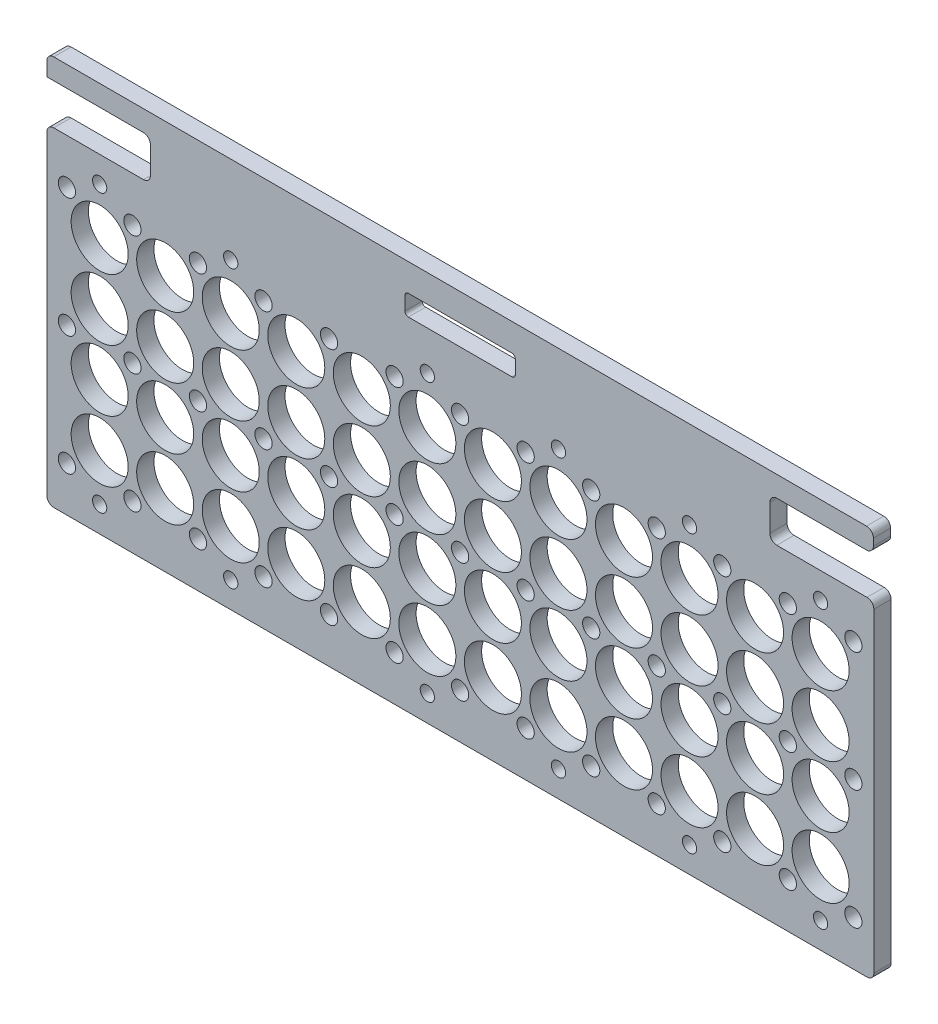
SolidWorks part; units mm, degrees
material "ABS"
ref_plane "X-Y Datum" through (0, 0, 0) normal (0, 0, 1) x (1, 0, 0)
ref_plane "X-Z Datum" through (0, 0, 0) normal (0, 1, 0) x (1, 0, 0)
ref_plane "Y-Z Datum" through (0, 0, 0) normal (1, 0, 0) x (0, 0, -1)
sketch "Sketch1" plane through (0, 0, 0) normal (0, 0, 1) x (1, 0, 0)
  line L1 (-10.2406, 8) -> (78.318, 8)
  line L2 (-10.2406, 8) -> (-10.2406, 16.1972)
  line L7 (-10.2406, 16.1972) -> (78.318, 16.1972)
  line L8 (78.318, 8) -> (78.318, 16.1972)
  line L12 (84.583, 16.1972) -> (87.883, 16.1972) construction
  line L17 (84.583, 4.7) -> (87.883, 4.7) construction
  line L20 (78.318, 0) -> (82.128, 0) construction
  circle A0 centre (0, 0) radius 10.5
  circle A24 centre (0, 0) radius 8 construction
  circle A25 centre (0, 0) radius 4.7 construction
  circle A46 centre (-3.5188, 13.3573) radius 2.5146 construction
  circle A47 centre (-3.5188, 13.3573) radius 1.1913 construction
  circle A78 centre (22.606, 0) radius 10.5
  circle A79 centre (22.606, 0) radius 8 construction
  circle A80 centre (22.606, 0) radius 4.7 construction
  circle A81 centre (45.212, 0) radius 10.5
  circle A82 centre (45.212, 0) radius 8 construction
  circle A83 centre (45.212, 0) radius 4.7 construction
  circle A84 centre (67.818, 0) radius 10.5
  circle A85 centre (67.818, 0) radius 8 construction
  circle A86 centre (67.818, 0) radius 4.7 construction
  circle A87 centre (0, 24.13) radius 10.5
  circle A88 centre (0, 24.13) radius 8 construction
  circle A89 centre (0, 24.13) radius 4.7 construction
  circle A90 centre (22.606, 24.13) radius 10.5
  circle A91 centre (22.606, 24.13) radius 8 construction
  circle A92 centre (22.606, 24.13) radius 4.7 construction
  circle A93 centre (45.212, 24.13) radius 10.5
  circle A94 centre (45.212, 24.13) radius 8 construction
  circle A95 centre (45.212, 24.13) radius 4.7 construction
  circle A96 centre (67.818, 24.13) radius 10.5
  circle A97 centre (67.818, 24.13) radius 8 construction
  circle A98 centre (67.818, 24.13) radius 4.7 construction
  circle A99 centre (0, 48.26) radius 10.5
  circle A100 centre (0, 48.26) radius 8 construction
  circle A101 centre (0, 48.26) radius 4.7 construction
  circle A102 centre (22.606, 48.26) radius 10.5
  circle A103 centre (22.606, 48.26) radius 8 construction
  circle A104 centre (22.606, 48.26) radius 4.7 construction
  circle A105 centre (45.212, 48.26) radius 10.5
  circle A106 centre (45.212, 48.26) radius 8 construction
  circle A107 centre (45.212, 48.26) radius 4.7 construction
  circle A108 centre (67.818, 48.26) radius 10.5
  circle A109 centre (67.818, 48.26) radius 8 construction
  circle A110 centre (67.818, 48.26) radius 4.7 construction
  circle A111 centre (0, 72.39) radius 10.5
  circle A112 centre (0, 72.39) radius 8 construction
  circle A113 centre (0, 72.39) radius 4.7 construction
  circle A114 centre (22.606, 72.39) radius 10.5
  circle A115 centre (22.606, 72.39) radius 8 construction
  circle A116 centre (22.606, 72.39) radius 4.7 construction
  circle A117 centre (45.212, 72.39) radius 10.5
  circle A118 centre (45.212, 72.39) radius 8 construction
  circle A119 centre (45.212, 72.39) radius 4.7 construction
  circle A120 centre (67.818, 72.39) radius 10.5
  circle A121 centre (67.818, 72.39) radius 8 construction
  circle A122 centre (67.818, 72.39) radius 4.7 construction
  circle A123 centre (0, 96.52) radius 10.5
  circle A124 centre (0, 96.52) radius 8 construction
  circle A125 centre (0, 96.52) radius 4.7 construction
  circle A126 centre (22.606, 96.52) radius 10.5
  circle A127 centre (22.606, 96.52) radius 8 construction
  circle A128 centre (22.606, 96.52) radius 4.7 construction
  circle A129 centre (45.212, 96.52) radius 10.5
  circle A130 centre (45.212, 96.52) radius 8 construction
  circle A131 centre (45.212, 96.52) radius 4.7 construction
  circle A132 centre (67.818, 96.52) radius 10.5
  circle A133 centre (67.818, 96.52) radius 8 construction
  circle A134 centre (67.818, 96.52) radius 4.7 construction
  circle A135 centre (0, 120.65) radius 10.5
  circle A136 centre (0, 120.65) radius 8 construction
  circle A137 centre (0, 120.65) radius 4.7 construction
  circle A138 centre (22.606, 120.65) radius 10.5
  circle A139 centre (22.606, 120.65) radius 8 construction
  circle A140 centre (22.606, 120.65) radius 4.7 construction
  circle A141 centre (45.212, 120.65) radius 10.5
  circle A142 centre (45.212, 120.65) radius 8 construction
  circle A143 centre (45.212, 120.65) radius 4.7 construction
  circle A144 centre (67.818, 120.65) radius 10.5
  circle A145 centre (67.818, 120.65) radius 8 construction
  circle A146 centre (67.818, 120.65) radius 4.7 construction
  dimension "D1" = 4
  dimension "D9" = 9.4
  dimension "D4" = 2.5
  dimension "D2" = 6
sketch "Sketch2" plane through (0, 0, 0) normal (0, 0, 1) x (1, 0, 0)
  line L0 (28.8471, 78.318) -> (28.8471, -10.5) construction
  line L5 (4.7, 78.318) -> (19.43, 78.318) construction
  line L6 (4.7, 78.318) -> (4.7, -10.5) construction
  line L7 (4.7, -10.5) -> (19.43, -10.5) construction
  line L8 (19.43, 78.318) -> (19.43, -10.5) construction
  line L9 (28.8471, 78.318) -> (43.5771, 78.318) construction
  line L10 (43.5771, 78.318) -> (43.5771, -10.5) construction
  line L11 (28.8471, -10.5) -> (43.5771, -10.5) construction
  line L12 (52.9942, 78.318) -> (52.9942, -10.5) construction
  line L13 (52.9942, 78.318) -> (67.7242, 78.318) construction
  line L14 (67.7242, 78.318) -> (67.7242, -10.5) construction
  line L15 (52.9942, -10.5) -> (67.7242, -10.5) construction
  line L16 (77.1413, 78.318) -> (77.1413, -10.5) construction
  line L17 (77.1413, 78.318) -> (91.8713, 78.318) construction
  line L18 (91.8713, 78.318) -> (91.8713, -10.5) construction
  line L19 (77.1413, -10.5) -> (91.8713, -10.5) construction
  line L20 (101.2884, 78.318) -> (101.2884, -10.5) construction
  line L21 (101.2884, 78.318) -> (116.0184, 78.318) construction
  line L22 (116.0184, 78.318) -> (116.0184, -10.5) construction
  line L23 (101.2884, -10.5) -> (116.0184, -10.5) construction
  line L24 (125.4355, 78.318) -> (125.4355, -10.5) construction
  line L25 (125.4355, 78.318) -> (140.1655, 78.318) construction
  line L26 (140.1655, 78.318) -> (140.1655, -10.5) construction
  line L27 (125.4355, -10.5) -> (140.1655, -10.5) construction
  line L28 (149.5826, 78.318) -> (149.5826, -10.5) construction
  line L29 (149.5826, 78.318) -> (164.3126, 78.318) construction
  line L30 (164.3126, 78.318) -> (164.3126, -10.5) construction
  line L31 (149.5826, -10.5) -> (164.3126, -10.5) construction
  line L32 (173.7297, 78.318) -> (173.7297, -10.5) construction
  line L33 (173.7297, 78.318) -> (188.4597, 78.318) construction
  line L34 (188.4597, 78.318) -> (188.4597, -10.5) construction
  line L35 (173.7297, -10.5) -> (188.4597, -10.5) construction
  line L36 (197.8768, 78.318) -> (197.8768, -10.5) construction
  line L37 (197.8768, 78.318) -> (212.6068, 78.318) construction
  line L38 (212.6068, 78.318) -> (212.6068, -10.5) construction
  line L39 (197.8768, -10.5) -> (212.6068, -10.5) construction
  line L40 (222.0239, 78.318) -> (222.0239, -10.5) construction
  line L41 (222.0239, 78.318) -> (236.7539, 78.318) construction
  line L42 (236.7539, 78.318) -> (236.7539, -10.5) construction
  line L43 (222.0239, -10.5) -> (236.7539, -10.5) construction
  line L44 (246.171, 78.318) -> (246.171, -10.5) construction
  line L45 (246.171, 78.318) -> (260.901, 78.318) construction
  line L46 (260.901, 78.318) -> (260.901, -10.5) construction
  line L47 (246.171, -10.5) -> (260.901, -10.5) construction
  line L48 (270.3181, 78.318) -> (270.3181, -10.5) construction
  line L49 (270.3181, 78.318) -> (285.0481, 78.318) construction
  line L50 (285.0481, 78.318) -> (285.0481, -10.5) construction
  line L51 (270.3181, -10.5) -> (285.0481, -10.5) construction
  line L52 (-19.43, 78.318) -> (-19.43, -10.5) construction
  line L53 (-19.43, 78.318) -> (-4.7, 78.318) construction
  line L54 (-4.7, 78.318) -> (-4.7, -10.5) construction
  line L55 (-19.43, -10.5) -> (-4.7, -10.5) construction
  line L56 (0, 78.3179) -> (0, 91.526) construction
  line L57 (0, -10.4999) -> (0, -23.708) construction
  line L58 (-27.6439, 33.909) -> (301.0934, 33.909) construction
  line L59 (-19.43, 91.526) -> (285.0481, 91.526) construction
  line L60 (-19.43, 91.526) -> (-19.43, -23.708)
  line L61 (-19.43, -23.708) -> (285.0481, -23.708) construction
  line L62 (285.0481, 91.526) -> (285.0481, -23.708)
  line L63 (-19.43, 91.526) -> (-19.43, 94.447)
  line L64 (-19.43, 94.447) -> (285.0481, 94.447)
  line L65 (285.0481, 94.447) -> (285.0481, 91.526)
  line L66 (-19.43, -23.708) -> (-19.43, -26.629)
  line L67 (-19.43, -26.629) -> (285.0481, -26.629)
  line L68 (285.0481, -26.629) -> (285.0481, -23.708)
  circle A0 centre (0, 0) radius 10.4999
  circle A8 centre (0, 0) radius 4.7 construction
  circle A10 centre (24.13, 0) radius 10.4999
  circle A11 centre (48.26, 0) radius 10.4999
  circle A12 centre (72.39, 0) radius 10.4999
  circle A13 centre (24.13, 22.606) radius 10.4999
  circle A14 centre (48.26, 22.606) radius 10.4999
  circle A15 centre (72.39, 22.606) radius 10.4999
  circle A16 centre (24.13, 45.212) radius 10.4999
  circle A17 centre (48.26, 45.212) radius 10.4999
  circle A18 centre (72.39, 45.212) radius 10.4999
  circle A19 centre (24.13, 67.818) radius 10.4999
  circle A20 centre (48.26, 67.818) radius 10.4999
  circle A21 centre (72.39, 67.818) radius 10.4999
  circle A28 centre (0, 22.606) radius 10.4999
  circle A29 centre (0, 45.212) radius 10.4999
  circle A30 centre (0, 67.818) radius 10.4999
  circle A33 centre (0, 0) radius 8 construction
  circle A34 centre (96.52, 0) radius 10.4999
  circle A35 centre (120.65, 0) radius 10.4999
  circle A36 centre (144.78, 0) radius 10.4999
  circle A37 centre (168.91, 0) radius 10.4999
  circle A38 centre (193.04, 0) radius 10.4999
  circle A39 centre (217.17, 0) radius 10.4999
  circle A40 centre (241.3, 0) radius 10.4999
  circle A41 centre (265.43, 0) radius 10.4999
  circle A42 centre (96.52, 22.606) radius 10.4999
  circle A43 centre (120.65, 22.606) radius 10.4999
  circle A44 centre (144.78, 22.606) radius 10.4999
  circle A45 centre (168.91, 22.606) radius 10.4999
  circle A46 centre (193.04, 22.606) radius 10.4999
  circle A47 centre (217.17, 22.606) radius 10.4999
  circle A48 centre (241.3, 22.606) radius 10.4999
  circle A49 centre (265.43, 22.606) radius 10.4999
  circle A50 centre (96.52, 45.212) radius 10.4999
  circle A51 centre (120.65, 45.212) radius 10.4999
  circle A52 centre (144.78, 45.212) radius 10.4999
  circle A53 centre (168.91, 45.212) radius 10.4999
  circle A54 centre (193.04, 45.212) radius 10.4999
  circle A55 centre (217.17, 45.212) radius 10.4999
  circle A56 centre (241.3, 45.212) radius 10.4999
  circle A57 centre (265.43, 45.212) radius 10.4999
  circle A58 centre (96.52, 67.818) radius 10.4999
  circle A59 centre (120.65, 67.818) radius 10.4999
  circle A60 centre (144.78, 67.818) radius 10.4999
  circle A61 centre (168.91, 67.818) radius 10.4999
  circle A62 centre (193.04, 67.818) radius 10.4999
  circle A63 centre (217.17, 67.818) radius 10.4999
  circle A64 centre (241.3, 67.818) radius 10.4999
  circle A65 centre (265.43, 67.818) radius 10.4999
  circle A82 centre (24.13, 0) radius 8 construction
  circle A83 centre (24.13, 0) radius 4.7 construction
  circle A84 centre (48.26, 0) radius 8 construction
  circle A85 centre (48.26, 0) radius 4.7 construction
  circle A86 centre (72.39, 0) radius 8 construction
  circle A87 centre (72.39, 0) radius 4.7 construction
  circle A88 centre (96.52, 0) radius 8 construction
  circle A89 centre (96.52, 0) radius 4.7 construction
  circle A90 centre (120.65, 0) radius 8 construction
  circle A91 centre (120.65, 0) radius 4.7 construction
  circle A92 centre (144.78, 0) radius 8 construction
  circle A93 centre (144.78, 0) radius 4.7 construction
  circle A94 centre (168.91, 0) radius 8 construction
  circle A95 centre (168.91, 0) radius 4.7 construction
  circle A96 centre (193.04, 0) radius 8 construction
  circle A97 centre (193.04, 0) radius 4.7 construction
  circle A98 centre (217.17, 0) radius 8 construction
  circle A99 centre (217.17, 0) radius 4.7 construction
  circle A100 centre (241.3, 0) radius 8 construction
  circle A101 centre (241.3, 0) radius 4.7 construction
  circle A102 centre (265.43, 0) radius 8 construction
  circle A103 centre (265.43, 0) radius 4.7 construction
  circle A104 centre (24.13, 22.606) radius 8 construction
  circle A105 centre (24.13, 22.606) radius 4.7 construction
  circle A106 centre (48.26, 22.606) radius 8 construction
  circle A107 centre (48.26, 22.606) radius 4.7 construction
  circle A108 centre (72.39, 22.606) radius 8 construction
  circle A109 centre (72.39, 22.606) radius 4.7 construction
  circle A110 centre (96.52, 22.606) radius 8 construction
  circle A111 centre (96.52, 22.606) radius 4.7 construction
  circle A112 centre (120.65, 22.606) radius 8 construction
  circle A113 centre (120.65, 22.606) radius 4.7 construction
  circle A114 centre (144.78, 22.606) radius 8 construction
  circle A115 centre (144.78, 22.606) radius 4.7 construction
  circle A116 centre (168.91, 22.606) radius 8 construction
  circle A117 centre (168.91, 22.606) radius 4.7 construction
  circle A118 centre (193.04, 22.606) radius 8 construction
  circle A119 centre (193.04, 22.606) radius 4.7 construction
  circle A120 centre (217.17, 22.606) radius 8 construction
  circle A121 centre (217.17, 22.606) radius 4.7 construction
  circle A122 centre (241.3, 22.606) radius 8 construction
  circle A123 centre (241.3, 22.606) radius 4.7 construction
  circle A124 centre (265.43, 22.606) radius 8 construction
  circle A125 centre (265.43, 22.606) radius 4.7 construction
  circle A126 centre (24.13, 45.212) radius 8 construction
  circle A127 centre (24.13, 45.212) radius 4.7 construction
  circle A128 centre (48.26, 45.212) radius 8 construction
  circle A129 centre (48.26, 45.212) radius 4.7 construction
  circle A130 centre (72.39, 45.212) radius 8 construction
  circle A131 centre (72.39, 45.212) radius 4.7 construction
  circle A132 centre (96.52, 45.212) radius 8 construction
  circle A133 centre (96.52, 45.212) radius 4.7 construction
  circle A134 centre (120.65, 45.212) radius 8 construction
  circle A135 centre (120.65, 45.212) radius 4.7 construction
  circle A136 centre (144.78, 45.212) radius 8 construction
  circle A137 centre (144.78, 45.212) radius 4.7 construction
  circle A138 centre (168.91, 45.212) radius 8 construction
  circle A139 centre (168.91, 45.212) radius 4.7 construction
  circle A140 centre (193.04, 45.212) radius 8 construction
  circle A141 centre (193.04, 45.212) radius 4.7 construction
  circle A142 centre (217.17, 45.212) radius 8 construction
  circle A143 centre (217.17, 45.212) radius 4.7 construction
  circle A144 centre (241.3, 45.212) radius 8 construction
  circle A145 centre (241.3, 45.212) radius 4.7 construction
  circle A146 centre (265.43, 45.212) radius 8 construction
  circle A147 centre (265.43, 45.212) radius 4.7 construction
  circle A148 centre (24.13, 67.818) radius 8 construction
  circle A149 centre (24.13, 67.818) radius 4.7 construction
  circle A150 centre (48.26, 67.818) radius 8 construction
  circle A151 centre (48.26, 67.818) radius 4.7 construction
  circle A152 centre (72.39, 67.818) radius 8 construction
  circle A153 centre (72.39, 67.818) radius 4.7 construction
  circle A154 centre (96.52, 67.818) radius 8 construction
  circle A155 centre (96.52, 67.818) radius 4.7 construction
  circle A156 centre (120.65, 67.818) radius 8 construction
  circle A157 centre (120.65, 67.818) radius 4.7 construction
  circle A158 centre (144.78, 67.818) radius 8 construction
  circle A159 centre (144.78, 67.818) radius 4.7 construction
  circle A160 centre (168.91, 67.818) radius 8 construction
  circle A161 centre (168.91, 67.818) radius 4.7 construction
  circle A162 centre (193.04, 67.818) radius 8 construction
  circle A163 centre (193.04, 67.818) radius 4.7 construction
  circle A164 centre (217.17, 67.818) radius 8 construction
  circle A165 centre (217.17, 67.818) radius 4.7 construction
  circle A166 centre (241.3, 67.818) radius 8 construction
  circle A167 centre (241.3, 67.818) radius 4.7 construction
  circle A168 centre (265.43, 67.818) radius 8 construction
  circle A169 centre (265.43, 67.818) radius 4.7 construction
  circle A170 centre (0, 22.606) radius 8 construction
  circle A171 centre (0, 22.606) radius 4.7 construction
  circle A172 centre (0, 45.212) radius 8 construction
  circle A173 centre (0, 45.212) radius 4.7 construction
  circle A174 centre (0, 67.818) radius 8 construction
  circle A175 centre (0, 67.818) radius 4.7 construction
  circle A178 centre (0, 84.922) radius 2.625
  circle A181 centre (48.26, 84.922) radius 2.625
  circle A188 centre (217.17, 84.922) radius 2.625
  circle A190 centre (265.43, 84.922) radius 2.625
  circle A191 centre (24.13, 84.922) radius 2.625 [skipped]
  circle A192 centre (72.39, 84.922) radius 2.625 [skipped]
  circle A193 centre (120.65, 84.922) radius 2.625
  circle A194 centre (193.04, 84.922) radius 2.625 [skipped]
  circle A195 centre (241.3, 84.922) radius 2.625 [skipped]
  circle A196 centre (168.91, 84.922) radius 2.625
  circle A197 centre (265.43, -17.104) radius 2.625
  circle A198 centre (217.17, -17.104) radius 2.625
  circle A201 centre (48.26, -17.104) radius 2.625
  circle A202 centre (0, -17.104) radius 2.625
  circle A203 centre (96.52, 84.922) radius 2.625 [skipped]
  circle A204 centre (144.78, 84.922) radius 2.625 [skipped]
  circle A205 centre (168.91, -17.104) radius 2.625
  circle A206 centre (120.65, -17.104) radius 2.625
  dimension "D1" = 12
  dimension "D3" = 12
  dimension "D5" = 12
  dimension "D2" = 4
  dimension "D4" = 2
extrude "Boss-Extrude1" add sketch "Sketch2" along normal blind 6.35
sketch "Sketch3" plane through (0, 0, 6.35) normal (0, 0, 1) x (1, 0, 0)
  line L0 (10.4999, 67.818) -> (13.6301, 67.818) construction
  line L1 (4.7, 78.318) -> (19.43, 78.318) construction
  line L2 (4.7, 78.318) -> (4.7, -10.5) construction
  line L3 (4.7, -10.5) -> (19.43, -10.5) construction
  line L4 (19.43, 78.318) -> (19.43, -10.5) construction
  line L5 (12.065, 67.818) -> (12.065, 78.318) construction
  line L6 (4.7, 33.909) -> (19.43, 33.909) construction
  line L7 (10.4999, 0) -> (13.6301, 0) construction
  circle A0 centre (0, 0) radius 4.7 construction
  circle A1 centre (0, 0) radius 6.2 construction
  circle A2 centre (0, 67.818) radius 10.4999 construction
  circle A3 centre (24.13, 67.818) radius 10.4999 construction
  circle A4 centre (12.065, 77.8952) radius 4.1656 construction
  circle A5 centre (12.065, 77.8952) radius 3.175
  circle A6 centre (12.065, -10.0772) radius 3.175
  circle A7 centre (12.065, -10.0772) radius 4.1656 construction
  circle A32 centre (36.195, 77.8952) radius 3.175
  circle A33 centre (60.325, 77.8952) radius 3.175
  circle A34 centre (84.455, 77.8952) radius 3.175
  circle A35 centre (108.585, 77.8952) radius 3.175
  circle A36 centre (132.715, 77.8952) radius 3.175
  circle A37 centre (156.845, 77.8952) radius 3.175
  circle A38 centre (180.975, 77.8952) radius 3.175
  circle A39 centre (205.105, 77.8952) radius 3.175
  circle A40 centre (229.235, 77.8952) radius 3.175
  circle A41 centre (253.365, 77.8952) radius 3.175
  circle A42 centre (277.495, 77.8952) radius 3.175
  circle A43 centre (-12.065, 77.8952) radius 3.175
  circle A44 centre (277.495, -10.0772) radius 3.175
  circle A45 centre (253.365, -10.0772) radius 3.175
  circle A46 centre (229.235, -10.0772) radius 3.175
  circle A47 centre (205.105, -10.0772) radius 3.175
  circle A48 centre (180.975, -10.0772) radius 3.175
  circle A49 centre (156.845, -10.0772) radius 3.175
  circle A50 centre (132.715, -10.0772) radius 3.175
  circle A51 centre (108.585, -10.0772) radius 3.175
  circle A52 centre (84.455, -10.0772) radius 3.175
  circle A53 centre (60.325, -10.0772) radius 3.175
  circle A54 centre (36.195, -10.0772) radius 3.175
  circle A55 centre (-12.065, -10.0772) radius 3.175
  circle A56 centre (12.065, 33.909) radius 3.175
  circle A57 centre (36.195, 33.909) radius 3.175
  circle A58 centre (60.325, 33.909) radius 3.175
  circle A59 centre (84.455, 33.909) radius 3.175
  circle A60 centre (108.585, 33.909) radius 3.175
  circle A61 centre (132.715, 33.909) radius 3.175
  circle A62 centre (156.845, 33.909) radius 3.175
  circle A63 centre (180.975, 33.909) radius 3.175
  circle A64 centre (205.105, 33.909) radius 3.175
  circle A65 centre (229.235, 33.909) radius 3.175
  circle A66 centre (253.365, 33.909) radius 3.175
  circle A67 centre (277.495, 33.909) radius 3.175
  circle A68 centre (-12.065, 33.909) radius 3.175
  circle A69 centre (0, 0) radius 10.4999 construction
  circle A70 centre (24.13, 0) radius 10.4999 construction
  dimension "D2" = 12
  dimension "D4" = 6.35
  dimension "D5" = 10.0772
  dimension "D6" = 10.0772
  dimension "D1" = 1.5
  dimension "D3" = 2
extrude "Cut-Extrude1" cut sketch "Sketch3" against normal through all
sketch "Sketch5" plane through (0, 0, 6.35) normal (0, 0, 1) x (1, 0, 0)
  line L1 (-19.43, 94.447) -> (-22.605, 94.447)
  line L2 (-19.43, 94.447) -> (-19.43, -26.629)
  line L3 (-19.43, -26.629) -> (-22.605, -26.629)
  line L4 (-22.605, 94.447) -> (-22.605, -26.629)
  line L5 (285.0481, 94.447) -> (288.2231, 94.447)
  line L6 (285.0481, 94.447) -> (285.0481, -26.629)
  line L7 (285.0481, -26.629) -> (288.2231, -26.629)
  line L8 (288.2231, 94.447) -> (288.2231, -26.629)
extrude "Boss-Extrude2" [suppressed] add sketch "Sketch5" against normal through all
sketch "Sketch6" [suppressed] plane through (0, 0, 6.35) normal (0, 0, 1) x (1, 0, 0)
  line L0 (-10.4999, 67.818) -> (275.9299, 67.818) construction
  circle A0 centre (0, 67.818) radius 10.4999 construction
  circle A1 centre (265.43, 67.818) radius 10.4999 construction
sketch "Sketch7" plane through (0, 0, 6.35) normal (0, 0, 1) x (1, 0, 0)
  line L0 (-19.43, -26.629) -> (0.3535, -26.629) construction
  line L1 (-19.43, -26.629) -> (285.0481, -26.629) construction
  line L10 (-19.43, 33.909) -> (302.2531, 33.909) construction
  line L11 (-19.43, 94.447) -> (-19.43, -26.629) construction
  line L12 (246.76, 93.177) -> (18.67, 93.177)
  line L16 (284.86, 117.064) -> (-19.43, 117.064)
  line L18 (-19.43, 117.064) -> (-19.43, 109.444)
  line L19 (-19.43, 109.444) -> (18.67, 109.444)
  line L20 (18.67, 109.444) -> (18.67, 93.177)
  line L21 (284.86, 117.064) -> (284.86, 109.444)
  line L22 (284.86, 109.444) -> (246.76, 109.444)
  line L23 (246.76, 109.444) -> (246.76, 93.177)
  line L24 (285.0481, 94.447) -> (-19.43, 94.447) construction
  dimension "D1" = 22.617
extrude "Boss-Extrude3" add sketch "Sketch7" against normal through all
sketch "Sketch8" [suppressed] plane through (0, 0, 6.35) normal (0, 0, 1) x (1, 0, 0)
  line L1 (-22.605, 94.447) -> (288.2231, 94.447)
  line L2 (-22.605, 94.447) -> (-22.605, 117.064)
  line L3 (-22.605, 117.064) -> (288.2231, 117.064)
  line L4 (288.2231, 94.447) -> (288.2231, 117.064)
extrude "Boss-Extrude4" [suppressed] add sketch "Sketch8" against normal through all
fillet "Fillet1" radius 2.54 11 edges at (18.67, 109.444, 3.175) (18.67, 94.447, 3.175) (-19.43, 94.447, 3.175) (285.0481, 94.447, 3.175) (246.76, 94.447, 3.175) (246.76, 109.444, 3.175) (284.86, 109.444, 3.175) (285.0481, -26.629, 3.175) (-19.43, -26.629, 3.175) (-19.43, 117.064, 3.175) (284.86, 117.064, 3.175)
fillet "Fillet2" [suppressed] radius 2.54
sketch "Sketch9" plane through (0, 0, 6.35) normal (0, 0, 1) x (1, 0, 0)
  line L0 (10.4999, 67.818) -> (12.065, 67.818) construction
  line L1 (0, 57.3181) -> (0, 55.7119) construction
  line L2 (12.065, 67.818) -> (12.065, 56.515) construction
  line L3 (0, 56.515) -> (12.065, 56.515) construction
  line L5 (48.26, 34.7121) -> (48.26, 33.1059) construction
  line L6 (48.26, 33.909) -> (36.195, 33.909) construction
  line L7 (36.195, 45.212) -> (36.195, 33.909) construction
  line L8 (12.065, 56.515) -> (36.195, 56.515)
  line L9 (12.065, 56.515) -> (12.065, 33.909)
  line L10 (12.065, 33.909) -> (36.195, 33.909)
  line L11 (36.195, 56.515) -> (36.195, 33.909)
  circle A0 centre (0, 67.818) radius 10.4999 construction
  circle A2 centre (0, 45.212) radius 10.4999 construction
  circle A4 centre (48.26, 45.212) radius 10.4999 construction
  circle A5 centre (48.26, 22.606) radius 10.4999 construction
sketch "Sketch10" plane through (0, 0, 6.35) normal (0, 0, 1) x (1, 0, 0)
  line L0 (132.715, 117.064) -> (132.715, 106.9616) construction
  line L1 (282.32, 117.064) -> (-16.89, 117.064) construction
  line L2 (132.715, 106.9616) -> (153.035, 106.9616)
  line L3 (153.035, 106.9616) -> (153.035, 99.3916)
  line L4 (153.035, 99.3916) -> (112.395, 99.3916)
  line L5 (112.395, 99.3916) -> (112.395, 106.9616)
  line L6 (112.395, 106.9616) -> (132.715, 106.9616)
extrude "Cut-Extrude2" cut sketch "Sketch10" against normal through all
fillet "Fillet3" radius 1.27 4 edges at (112.395, 99.3916, 3.175) (153.035, 99.3916, 3.175) (153.035, 106.9616, 3.175) (112.395, 106.9616, 3.175)
